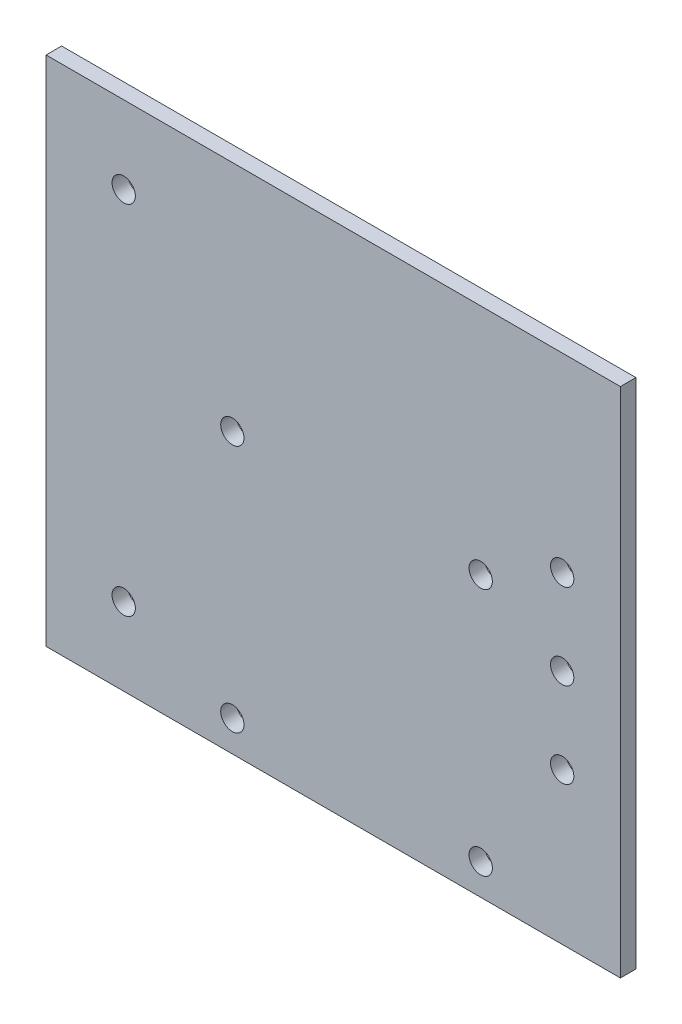
SolidWorks part; units mm, degrees
ref_plane "Plan de face" through (0, 0, 0) normal (0, 0, 1) x (1, 0, 0)
ref_plane "Plan de dessus" through (0, 0, 0) normal (0, 1, 0) x (1, 0, 0)
ref_plane "Plan de droite" through (0, 0, 0) normal (1, 0, 0) x (0, 0, -1)
sketch "Esquisse1" plane through (0, 0, 0) normal (0, 0, 1) x (1, 0, 0)
  line L1 (-28.1681, 19.2932) -> (45.8319, 19.2932)
  line L2 (-28.1681, 19.2932) -> (-28.1681, -46.7068)
  line L3 (-28.1681, -46.7068) -> (45.8319, -46.7068)
  line L4 (45.8319, 19.2932) -> (45.8319, -46.7068)
  circle A0 centre (-18.1681, 9.2932) radius 1.5
  circle A1 centre (-18.1681, -36.7068) radius 1.5
  circle A2 centre (38.3319, -5.2068) radius 1.5
  circle A3 centre (38.3319, -27.2068) radius 1.5
  circle A4 centre (38.3319, -16.2068) radius 1.5
  dimension "D3" = 10
  dimension "D9" = 19.5
  dimension "D10" = 11
  dimension "D1" = 74
  dimension "D2" = 66
  dimension "D4" = 10
  dimension "D5" = 10
  dimension "D6" = 10
  dimension "D7" = 7.5
  dimension "D8" = 24.5
extrude "Extrusion1" add sketch "Esquisse1" along normal blind 2
sketch "Esquisse2" plane through (0, 0, 2) normal (0, 0, 1) x (1, 0, 0)
  line L0 (45.8319, -46.7068) -> (45.8319, 19.2932) construction
  line L1 (-4.1681, -10.7068) -> (27.8319, -10.7068) construction
  line L2 (-4.1681, -10.7068) -> (-4.1681, -42.7068) construction
  line L3 (-4.1681, -42.7068) -> (27.8319, -42.7068) construction
  line L4 (27.8319, -10.7068) -> (27.8319, -42.7068) construction
  line L5 (-28.1681, -46.7068) -> (45.8319, -46.7068) construction
  circle A0 centre (27.8319, -10.7068) radius 1.5
  circle A1 centre (-4.1681, -10.7068) radius 1.5
  circle A2 centre (-4.1681, -42.7068) radius 1.5
  circle A3 centre (27.8319, -42.7068) radius 1.5
  dimension "D1" = 32
  dimension "D2" = 32
  dimension "D3" = 18
  dimension "D4" = 4
extrude "Extrusion2" cut sketch "Esquisse2" against normal blind 10
